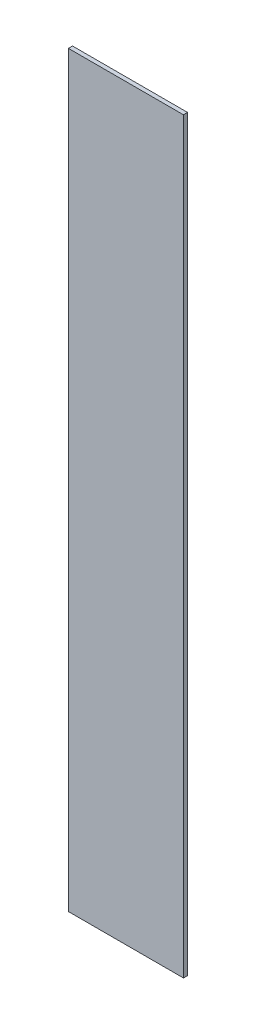
SolidWorks part; units mm, degrees
ref_plane "Front Plane" through (0, 0, 0) normal (0, 0, 1) x (1, 0, 0)
ref_plane "Top Plane" through (0, 0, 0) normal (0, 1, 0) x (1, 0, 0)
ref_plane "Right Plane" through (0, 0, 0) normal (1, 0, 0) x (0, 0, -1)
other "Configuration Table"
sketch "Sketch1" plane through (0, 0, 0) normal (0, 0, 1) x (1, 0, 0)
  line L1 (133, 879) -> (161, 879)
  line L2 (133, 879) -> (133, 1061)
  line L3 (133, 1061) -> (161, 1061)
  line L4 (161, 879) -> (161, 1061)
extrude "OVEN_yag_kabi_kapagi_kulp_cukuru_1" add sketch "Sketch1" along normal blind 1 from offset 26 separate body
